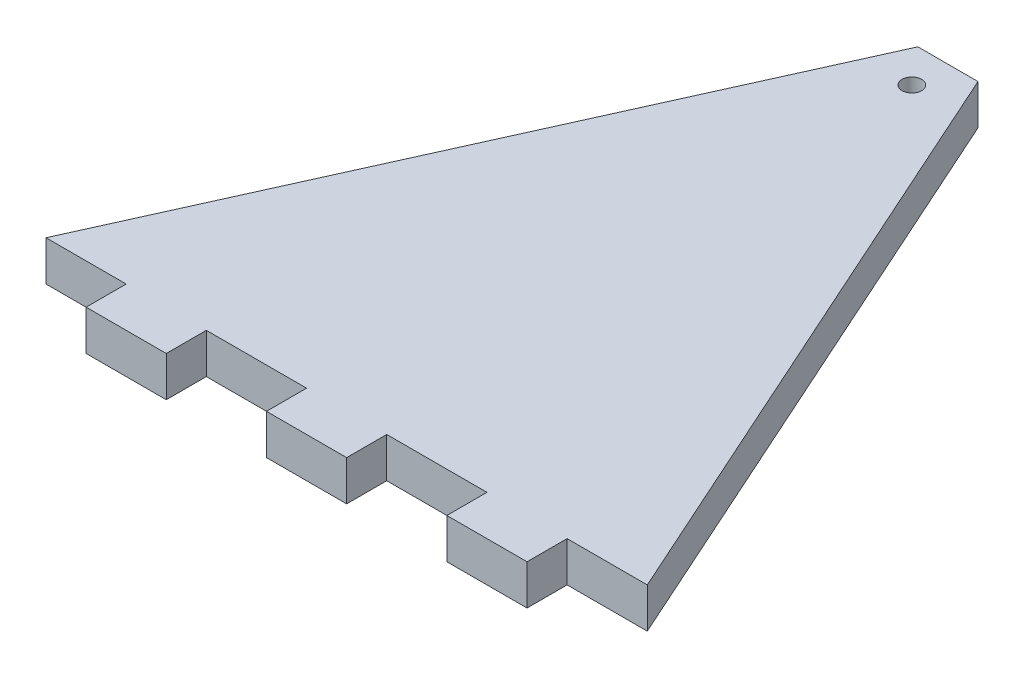
SolidWorks part; units mm, degrees
material "ABS PC"
ref_plane "Front Plane" through (0, 0, 0) normal (0, 0, 1) x (1, 0, 0)
ref_plane "Top Plane" through (0, 0, 0) normal (0, 1, 0) x (1, 0, 0)
ref_plane "Right Plane" through (0, 0, 0) normal (1, 0, 0) x (0, 0, -1)
sketch "Sketch1" plane through (0, 0, 0) normal (0, 1, 0) x (1, 0, 0)
  line L0 (0, 75) -> (0, 66) construction
  line L3 (-7.5, 75) -> (7.5, 75)
  line L5 (-7.5, -75) -> (7.5, 75) construction
  line L6 (-7.5, 75) -> (7.5, -75) construction
  line L7 (-35, -75) -> (-10, -75)
  line L8 (-75, -75) -> (-7.5, 75)
  line L9 (7.5, 75) -> (75, -75)
  line L10 (0, -75) -> (0, 75) construction
  line L14 (55, -75) -> (55, -85)
  line L16 (-55, -75) -> (-55, -85)
  line L18 (10, -75) -> (35, -75)
  line L20 (10, -75) -> (10, -85)
  line L21 (10, -85) -> (-10, -85)
  line L22 (-10, -75) -> (-10, -85)
  line L23 (6.8182, -68.1818) -> (-10, -85) construction
  line L24 (10, -85) -> (-6.8182, -68.1818) construction
  line L25 (55, -75) -> (75, -75)
  line L27 (35, -75) -> (35, -85)
  line L28 (35, -85) -> (55, -85)
  line L29 (55, -75) -> (55, -85)
  line L31 (-55, -75) -> (-55, -85)
  line L32 (-55, -85) -> (-35, -85)
  line L33 (-35, -75) -> (-35, -85)
  line L34 (-55, -75) -> (-75, -75)
  circle A0 centre (0, 66) radius 2.45
  point P0 (0, 0)
  point P12 (0, -75)
  dimension "D3" = 4.9
  dimension "D1" = 15
  dimension "D2" = 9
  dimension "25" = 150
  dimension "D4" = 150
  dimension "D7" = 20
  dimension "D8" = 20
  dimension "D9" = 20
extrude "Boss-Extrude1" add sketch "Sketch1" along normal blind 10
